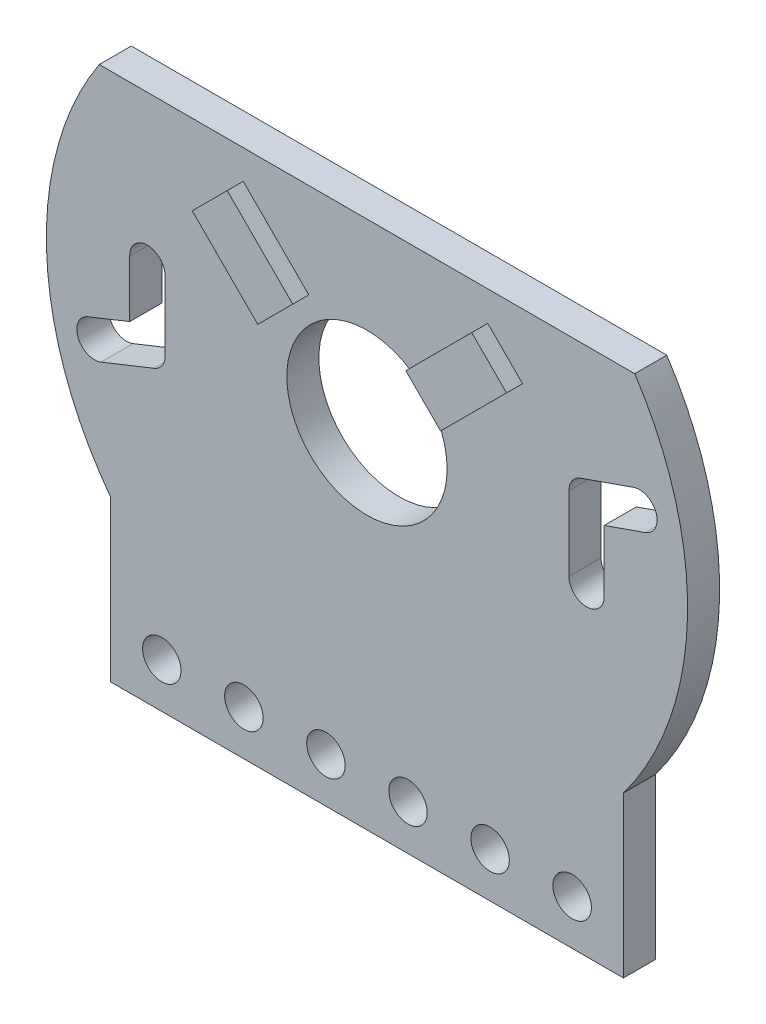
SolidWorks part; units mm, degrees
ref_plane "Plan de face" through (0, 0, 0) normal (0, 0, 1) x (1, 0, 0)
ref_plane "Plan de dessus" through (0, 0, 0) normal (0, 1, 0) x (1, 0, 0)
ref_plane "Plan de droite" through (0, 0, 0) normal (1, 0, 0) x (0, 0, -1)
sketch "Esquisse1" plane through (0, 0, 0) normal (0, 0, 1) x (1, 0, 0)
  line L0 (-9.5524, 0) -> (10.7605, 0) construction
  line L1 (0, 6.227) -> (0, -13.0879) construction
  line L2 (-8.3516, 5.5) -> (8.3516, 5.5)
  line L3 (-8, -6) -> (-8, -11)
  line L4 (-8, -11) -> (8, -11)
  line L5 (8, -11) -> (8, -6)
  line L6 (-10.7456, -9.6) -> (9.9861, -9.6) construction
  line L7 (-6.85, 0.8204) -> (-6.85, -1.3296) construction
  line L8 (-6.3, 0.8) -> (-6.3, -1.4442)
  line L9 (-7.4, 0.8) -> (-7.4, -0.9694)
  line L10 (-6.85, -1.3296) -> (-8.5, -2) construction
  line L11 (-6.642, -1.8514) -> (-8.293, -2.5096)
  line L12 (-7.4, -0.9694) -> (-8.707, -1.4904)
  line L13 (-5.7905, 0.8) -> (-7.65, 0.8) construction
  line L14 (6.85, 1.3154) -> (6.85, -1) construction
  line L15 (7.4, 1.3154) -> (7.4, -1)
  line L16 (6.3, 1.3154) -> (6.3, -1)
  line L17 (6.85, 1.3154) -> (11.27, 3.5613) construction
  line L18 (6.85, 2.2328) -> (6.85, -2.7816) construction
  line L19 (5.5719, 0.8) -> (8.2201, 0.8) construction
  line L23 (8.3839, 2.7117) -> (8.8822, 1.7311) construction
  circle A0 centre (0, 0) radius 2.5
  arc A1 (-8.3516, 5.5) -> (-8, -6) centre (0, 0) ccw
  arc A2 (8, -6) -> (8.3516, 5.5) centre (0, 0) ccw
  circle A3 centre (-6.4, -9.6) radius 0.6
  circle A4 centre (-3.84, -9.6) radius 0.6
  circle A5 centre (-1.28, -9.6) radius 0.6
  circle A6 centre (1.28, -9.6) radius 0.6
  circle A7 centre (3.84, -9.6) radius 0.6
  circle A8 centre (6.4, -9.6) radius 0.6
  arc A9 (-6.3, 0.8) -> (-7.4, 0.8) centre (-6.85, 0.8204) ccw
  arc A10 (7.4, 1.3154) -> (6.3, 1.3154) centre (6.85, 1.3154) ccw
  arc A11 (-6.642, -1.8514) -> (-6.3, -1.4442) centre (-6.85, -1.3296) ccw
  arc A12 (-8.707, -1.4904) -> (-8.293, -2.5096) centre (-8.5, -2) ccw
  arc A13 (6.3, -1) -> (7.4, -1) centre (6.85, -1) ccw
  point P17 (-8, -8.5)
  point P37 (-7.675, -1.6648)
  point P50 (6.85, 0.1577)
  dimension "D1" = 5
  dimension "D2" = 20
  dimension "D7" = 1.2
  dimension "D22" = 6.85
  dimension "D3" = 5.5
  dimension "D4" = 16
  dimension "D5" = 11
  dimension "D6" = 1.4
  dimension "D8" = 1.6
  dimension "D10" = 1.1
  dimension "D11" = 1.1
  dimension "D13" = 2.15
  dimension "D14" = 7.5
  dimension "D15" = 8.5
  dimension "D16" = 6.85
  dimension "D17" = 4.7
  dimension "D19" = 1.3154
  dimension "D20" = 1
  dimension "D23" = 1.1
  dimension "D9" = 6
extrude "Boss.-Extru.1" add sketch "Esquisse1" along normal blind 1
sketch "Esquisse2" plane through (0, 0, 1) normal (0, 0, 1) x (1, 0, 0)
  line L0 (6.85, 1.3154) -> (8.499, 1.8926) construction
  line L1 (6.6683, 1.8345) -> (8.3173, 2.4117)
  line L2 (7.0317, 0.7963) -> (8.6807, 1.3734)
  arc A0 (6.6683, 1.8345) -> (7.0317, 0.7963) centre (6.85, 1.3154) ccw
  arc A1 (8.6807, 1.3734) -> (8.3173, 2.4117) centre (8.499, 1.8926) ccw
  arc A2 (7.4, 1.3154) -> (6.3, 1.3154) centre (6.85, 1.3154) ccw construction
  point P2 (7.6745, 1.604)
  dimension "D1" = 1.1
extrude "Enlèv. mat.-Extru.1" cut sketch "Esquisse2" against normal through all
sketch "Esquisse3" plane through (0, 0, 1) normal (0, 0, 1) x (1, 0, 0)
  line L0 (-4.9508, 3.4988) -> (-2.9062, 1.4542)
  line L1 (-2.9062, 1.4542) -> (-1.8149, 2.5454)
  line L2 (-1.8149, 2.5454) -> (-3.8596, 4.5901)
  line L3 (-3.8596, 4.5901) -> (-4.9508, 3.4988)
extrude "Boss.-Extru.2" add sketch "Esquisse3" along normal blind 0.5
sketch "Esquisse4" plane through (0, 0, 1) normal (0, 0, 1) x (1, 0, 0)
  line L0 (1.7115, 2.511) -> (3.7677, 4.5671)
  line L1 (3.7677, 4.5671) -> (4.8532, 3.4816)
  line L2 (4.8532, 3.4816) -> (2.797, 1.4255)
  line L3 (2.797, 1.4255) -> (1.7115, 2.511)
extrude "Boss.-Extru.3" add sketch "Esquisse4" along normal blind 0.5
